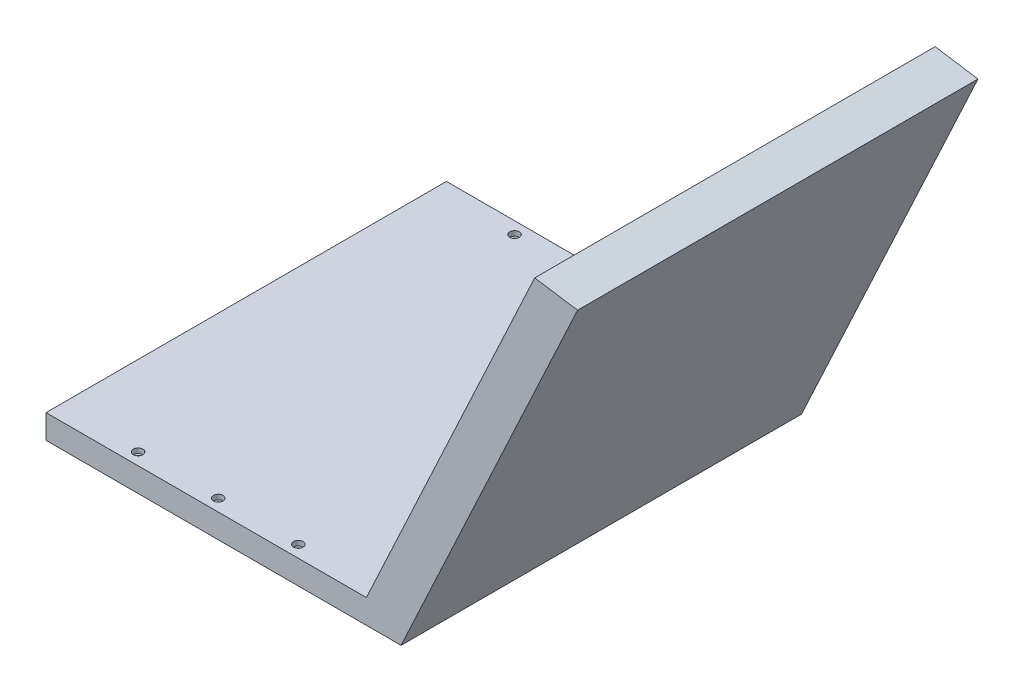
SolidWorks part; units mm, degrees
ref_plane "Front Plane" through (0, 0, 0) normal (0, 0, 1) x (1, 0, 0)
ref_plane "Top Plane" through (0, 0, 0) normal (0, 1, 0) x (1, 0, 0)
ref_plane "Right Plane" through (0, 0, 0) normal (1, 0, 0) x (0, 0, -1)
sketch "Sketch2" plane through (0, 0, 0) normal (0, 0, 1) x (1, 0, 0)
  line L8 (0, 0) -> (-443.3492, 0)
  line L9 (0, 0) -> (220.3586, 472.5606)
  line L13 (-443.3492, 30) -> (-43.3492, 30)
  line L14 (-43.3492, 30) -> (166.8726, 480.8219)
  line L15 (166.8726, 480.8219) -> (220.3586, 472.5606)
  line L16 (-443.3492, 30) -> (-443.3492, 0)
  dimension "D3" = 400
  dimension "D5" = 30
  dimension "D6" = 65
extrude "Boss-Extrude2" add sketch "Sketch2" along normal mid plane 500
sketch "Sketch5" plane through (0, 30, 0) normal (0, 1, 0) x (1, 0, 0)
  line L0 (-243.3492, 250) -> (-243.3492, -250) construction
  line L1 (-43.3492, 250) -> (-443.3492, 250) construction
  line L2 (-43.3492, -250) -> (-443.3492, -250) construction
  line L3 (-243.3492, 0) -> (-43.3492, 0) construction
  line L5 (-43.3492, -250) -> (-43.3492, 250) construction
  line L6 (-143.3492, 0) -> (-143.3492, -250) construction
  line L7 (-243.3492, 0) -> (-443.3492, 0) construction
  line L8 (-443.3492, -250) -> (-443.3492, 250) construction
  line L9 (-343.3492, 0) -> (-343.3492, -250) construction
  circle A0 centre (-343.3492, -235) radius 6
  circle A1 centre (-243.3492, -235) radius 6
  circle A2 centre (-143.3492, -235) radius 6
  circle A3 centre (-143.3492, 235) radius 6
  circle A4 centre (-243.3492, 235) radius 6
  circle A5 centre (-343.3492, 235) radius 6
  dimension "D2" = 12
  dimension "D1" = 12
  dimension "D3" = 12
  dimension "D4" = 15
  dimension "D5" = 15
  dimension "D6" = 15
extrude "Cut-Extrude1" cut sketch "Sketch5" against normal blind 6
sketch "Sketch6" plane through (0, 24, 0) normal (0, 1, 0) x (1, 0, 0)
  circle A0 centre (-143.3492, 235) radius 3
  circle A1 centre (-243.3492, 235) radius 3
  circle A2 centre (-343.3492, 235) radius 3
  circle A3 centre (-343.3492, -235) radius 3
  circle A4 centre (-243.3492, -235) radius 3
  circle A5 centre (-143.3492, -235) radius 3
  dimension "D1" = 6
  dimension "D3" = 6
  dimension "D2" = 3
  dimension "D4" = 3
extrude "Cut-Extrude2" cut sketch "Sketch6" against normal through all
